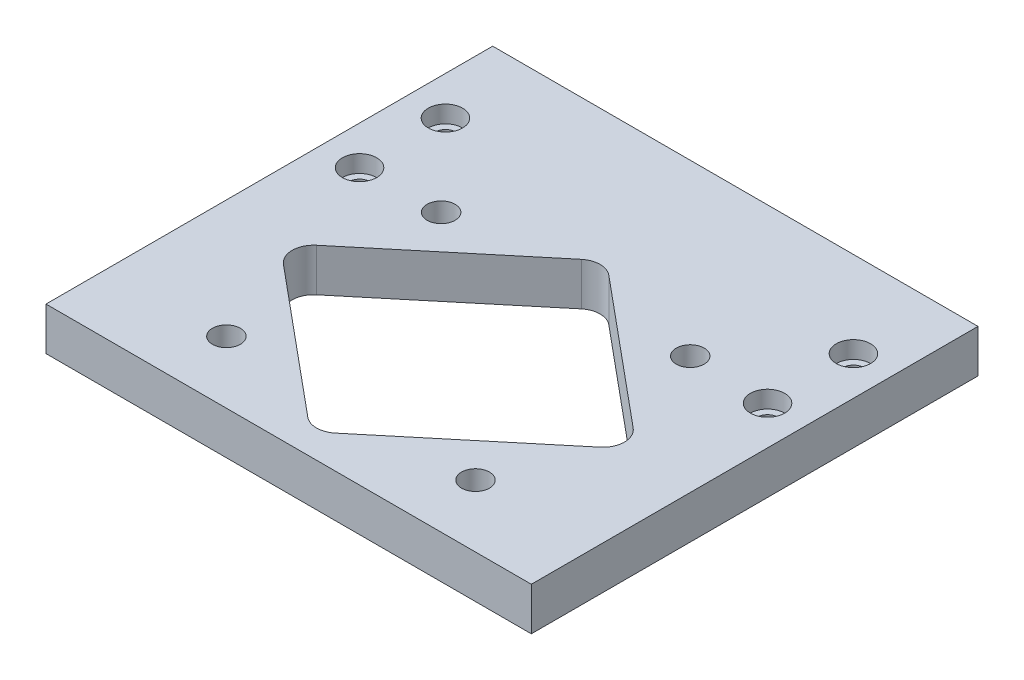
SolidWorks part; units mm, degrees
ref_plane "Front Plane" through (0, 0, 0) normal (0, 0, 1) x (1, 0, 0)
ref_plane "Top Plane" through (0, 0, 0) normal (0, 1, 0) x (1, 0, 0)
ref_plane "Right Plane" through (0, 0, 0) normal (1, 0, 0) x (0, 0, -1)
sketch "StageReference" plane through (0, 0, 0) normal (0, 1, 0) x (1, 0, 0)
  line L0 (0, 41.2036) -> (0, -45.2655) construction
  line L1 (-36.5, -29.5) -> (36.5, -29.5)
  line L2 (-36.5, -29.5) -> (-36.5, 29.5)
  line L3 (-36.5, 29.5) -> (36.5, 29.5)
  line L4 (36.5, -29.5) -> (36.5, 29.5)
  line L5 (-36.5, -29.5) -> (36.5, 29.5) construction
  line L6 (-36.5, 29.5) -> (36.5, -29.5) construction
  line L7 (-66.8139, 0) -> (103.4377, 0) construction
  line L10 (35.5, -5.3212) -> (35.5, -19.5)
  line L11 (35.5, -19.5) -> (24.0575, -19.5)
  line L12 (-35.5, 12.051) -> (-35.5, 19.5)
  line L13 (-35.5, 19.5) -> (-21.6263, 19.5)
  circle A0 centre (-29, -25) radius 3.25
  circle A1 centre (29, -25) radius 3.25
  circle A2 centre (29, 25) radius 3.25
  circle A3 centre (-29, 25) radius 3.25
  circle A4 centre (32.25, -16.25) radius 3.25
  circle A6 centre (-32.25, 16.25) radius 3.25
  point P0 (0, 0)
  dimension "D3" = 6.5
  dimension "D8" = 6.5
  dimension "D9" = 6.5
  dimension "D1" = 59
  dimension "D2" = 73
  dimension "D4" = 4.5
  dimension "D5" = 7.5
  dimension "D6" = 10
  dimension "D7" = 1
  dimension "D10" = 1
  dimension "D11" = 10
sketch "Sketch2" plane through (0, 0, 0) normal (0, 1, 0) x (1, 0, 0)
  line L0 (0, 41.2036) -> (0, -45.2655) construction
  line L1 (-56.5, -39.5) -> (56.5, -39.5)
  line L2 (-56.5, -39.5) -> (-56.5, 64.5)
  line L3 (-56.5, 64.5) -> (56.5, 64.5)
  line L4 (56.5, -39.5) -> (56.5, 64.5)
  line L5 (-56.5, -39.5) -> (56.5, 64.5) construction
  line L6 (-56.5, 64.5) -> (56.5, -39.5) construction
  line L7 (-36.5, 29.5) -> (36.5, 29.5) construction
  line L8 (-36.5, -29.5) -> (36.5, -29.5) construction
  line L9 (-36.5, -29.5) -> (-36.5, 29.5) construction
  point P0 (0, 12.5)
  dimension "D1" = 20
  dimension "D2" = 35
  dimension "D3" = 10
  dimension "D4" = 113
extrude "Top Face" add sketch "Sketch2" along normal blind 10
sketch "Sketch3" plane through (0, 0, 0) normal (0, -1, 0) x (1, 0, 0)
  circle A0 centre (-29, 25) radius 3.25 construction
  circle A1 centre (-29, -25) radius 3.25 construction
  circle A2 centre (29, -25) radius 3.25 construction
  circle A3 centre (29, 25) radius 3.25 construction
  circle A4 centre (-29, 25) radius 3.25
  circle A5 centre (-29, -25) radius 3.25
  circle A6 centre (29, -25) radius 3.25
  circle A7 centre (29, 25) radius 3.25
extrude "Cut-Extrude1" cut sketch "Sketch3" against normal blind 10
sketch "Sketch4" plane through (0, 10, 0) normal (0, 1, 0) x (1, 0, 0)
  line L0 (0, 34.5) -> (-41.5, 0)
  line L1 (0, 34.5) -> (41.5, 0)
  line L2 (-41.5, 0) -> (0, -34.5)
  line L3 (41.5, 0) -> (0, -34.5)
  line L4 (0, 34.5) -> (0, -34.5) construction
  line L5 (-41.5, 0) -> (41.5, 0) construction
  line L6 (-66.8139, 0) -> (103.4377, 0) construction
  point P1 (0, 0)
  dimension "D1" = 69
  dimension "D2" = 83
extrude "Cut-Extrude2" cut sketch "Sketch4" against normal blind 10
fillet "Fillet1" radius 5 4 edges at (0, 5, -34.5) (-41.5, 5, 0) (41.5, 5, 0) (0, 5, 34.5)
sketch "Mounting Plate Holes" plane through (0, 10, 0) normal (0, 1, 0) x (1, 0, 0)
  line L0 (47.5, 14.5) -> (47.5, 54.5) construction
  line L1 (56.5, 54.5) -> (38.5, 54.5)
  line L2 (56.5, 54.5) -> (56.5, 14.5)
  line L3 (56.5, 14.5) -> (38.5, 14.5)
  line L4 (38.5, 54.5) -> (38.5, 14.5)
  line L5 (0, -84.2055) -> (0, 76.6184) construction
  line L6 (-47.5, 14.5) -> (-47.5, 54.5) construction
  line L7 (-38.5, 54.5) -> (-38.5, 14.5)
  line L8 (-56.5, 14.5) -> (-38.5, 14.5)
  line L9 (-56.5, 54.5) -> (-56.5, 14.5)
  line L10 (-56.5, 54.5) -> (-38.5, 54.5)
  line L12 (56.5, -39.5) -> (56.5, 64.5) construction
  line L13 (56.5, 64.5) -> (-56.5, 64.5) construction
  point P7 (47.5, 24.5)
  point P8 (47.5, 44.5)
  point P18 (-47.5, 44.5)
  point P19 (-47.5, 24.5)
  dimension "D1" = 18
  dimension "D2" = 20
  dimension "D3" = 10
  dimension "D4" = 40
  dimension "D5" = 10
hole_wizard "CBORE for M4 SHCS1" positions "Sketch6" profile "Sketch7" counterbore size "M4" standard "ANSI Metric" end condition up to next
sketch "Sketch6" plane through (0, 10, 0) normal (0, 1, 0) x (1, 0, 0)
  point P0 (47.5, 44.5)
  point P3 (47.5, 24.5)
  point P6 (-47.5, 24.5)
  point P9 (-47.5, 44.5)
sketch "Sketch7" plane through (47.5, 10, -44.5) normal (1, 0, 0) x (0, 0, 1)
  line L0 (0, 0) -> (0, 10)
  line L1 (0, 10) -> (2.4, 10)
  line L3 (2.4, 10) -> (2.4, 4)
  line L4 (2.4, 4) -> (4, 4)
  line L5 (4, 4) -> (4, 0)
  line L7 (4, 0) -> (0, 0)
  line L11 (0, -6.35) -> (0, 107.95) construction
  dimension "Thru Hole Dia." = 4.8
  dimension "Thru Hole Depth" = 10
  dimension "C'Bore Dia." = 8
  dimension "C'Bore Depth" = 4
equation "\"MountingPlateThickness\"=10"
equation "\"D5@Mounting Plate Holes\"=\"MountingPlateThickness\""
